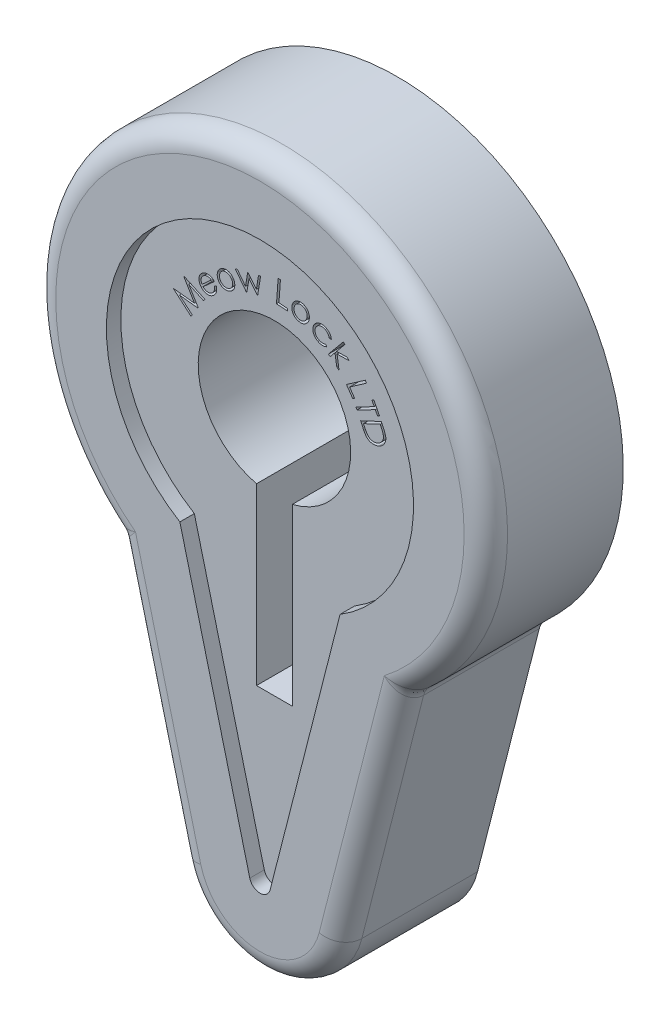
SolidWorks part; units mm, degrees
material "Brass"
ref_plane "Front Plane" through (0, 0, 0) normal (0, 0, 1) x (1, 0, 0)
ref_plane "Top Plane" through (0, 0, 0) normal (0, 1, 0) x (1, 0, 0)
ref_plane "Right Plane" through (0, 0, 0) normal (1, 0, 0) x (0, 0, -1)
sketch "Sketch1" plane through (0, 0, 0) normal (0, 0, 1) x (1, 0, 0)
  line L1 (-19.8654, 14.3237) -> (-11.0929, -19.9924)
  line L2 (19.8654, 14.3237) -> (11.0929, -19.9924)
  arc A0 (-11.0929, -19.9924) -> (11.0929, -19.9924) centre (0, -17.1566) ccw
  arc A1 (-19.8654, 14.3237) -> (19.8654, 14.3237) centre (0, 38.4255) cw
extrude "Boss-Extrude1" add sketch "Sketch1" along normal blind 19 contours A1 L2 A0 L1
fillet "Fillet1" radius 3 3 edges at (-15.4791, -2.8343, 19) (15.4791, -2.8343, 19) (0, -28.6062, 19)
fillet "Fillet2" radius 3 1 edges at (0, 69.6591, 19)
fillet "Fillet3" radius 3 4 edges at (-19.3304, 14.6647, 17.8038) (19.3304, 14.6647, 17.8038) (-19.8654, 14.3237, 8) (19.8654, 14.3237, 8)
sketch "Sketch2" plane through (0, 0, 19) normal (0, 0, 1) x (1, 0, 0)
  line L4 (1.4044, -17.5156) -> (11.0737, 20.3083)
  line L5 (-11.0737, 20.3083) -> (-1.4044, -17.5156)
  line L6 (1.4044, -17.5156) -> (11.0737, 20.3083)
  line L7 (-11.0737, 20.3083) -> (-1.4044, -17.5156)
  arc A4 (11.0737, 20.3083) -> (-11.0737, 20.3083) centre (0, 38.4255) ccw
  arc A5 (-1.4044, -17.5156) -> (1.4044, -17.5156) centre (0, -17.1566) ccw
  arc A6 (11.0737, 20.3083) -> (-11.0737, 20.3083) centre (0, 38.4255) ccw
  arc A7 (-1.4044, -17.5156) -> (1.4044, -17.5156) centre (0, -17.1566) ccw
  dimension "D1" = 7
extrude "Cut-Extrude1" cut sketch "Sketch2" against normal blind 2
sketch "Sketch3" plane through (0, 0, 17) normal (0, 0, 1) x (1, 0, 0)
  line L2 (-2.4744, 28.1807) -> (-2.4744, 4.0132)
  line L3 (-2.4744, 4.0132) -> (2.4744, 4.0132)
  line L4 (2.4744, 28.1807) -> (2.4744, 4.0132)
  line L5 (0, 27.8861) -> (2.4744, 4.0132) construction
  line L6 (-2.4744, 4.0132) -> (0, 27.8861) construction
  arc A0 (2.4744, 28.1807) -> (-2.4744, 28.1807) centre (0, 38.4255) ccw
  point P3 (0, 27.8861)
extrude "Cut-Extrude2" cut sketch "Sketch3" against normal through all
sketch "Sketch4" plane through (0, 0, 17) normal (0, 0, 1) x (1, 0, 0)
  arc A0 (-11.658, 43.4961) -> (11.8773, 42.9586) centre (0, 38.4255) cw construction
  text T0 "Meow Lock LTD"
extrude "Cut-Extrude3" cut sketch "Sketch4" against normal blind 2
